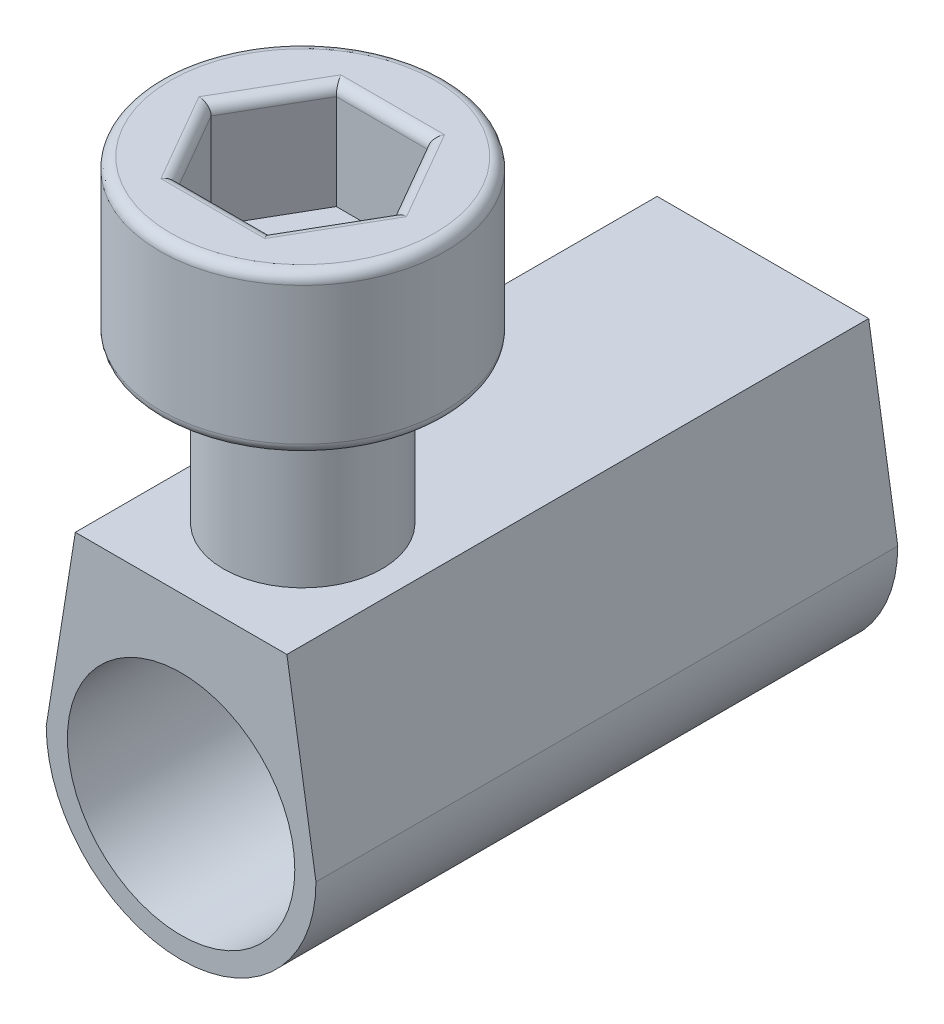
SolidWorks part; units mm, degrees
ref_plane "Спереди" through (0, 0, 0) normal (0, 0, 1) x (1, 0, 0)
ref_plane "Сверху" through (0, 0, 0) normal (0, 1, 0) x (1, 0, 0)
ref_plane "Справа" through (0, 0, 0) normal (1, 0, 0) x (0, 0, -1)
sketch "Эскиз1" plane through (0, 0, 0) normal (0, 0, 1) x (1, 0, 0)
  line L0 (-2, 6) -> (2, 6)
  line L1 (2, 6) -> (2.55, 2.55)
  line L3 (-2.55, 2.55) -> (-2, 6)
  circle A0 centre (0, 2.55) radius 2.15
  circle A1 centre (0, 2.55) radius 2.55 construction
  arc A2 (2.55, 2.55) -> (-2.55, 2.55) centre (0, 2.55) cw
  point P3 (0, 6)
  point P5 (0, 0)
  dimension "D2" = 2.55
  dimension "D3" = 4.3
  dimension "D1" = 6
  dimension "D4" = 4
extrude "Бобышка-Вытянуть1" add sketch "Эскиз1" against normal blind 11
sketch "Эскиз2" plane through (0, 6, 0) normal (0, 1, 0) x (1, 0, 0)
  line L0 (2, 0) -> (-2, 0) construction
  circle A0 centre (0, 2.3) radius 1.5
  dimension "D1" = 2.3
  dimension "D2" = 3
extrude "Вырез-Вытянуть1" cut sketch "Эскиз2" against normal up to next
sketch "Эскиз3" plane through (0, 6, 0) normal (0, 1, 0) x (1, 0, 0)
  circle A0 centre (0, 2.3) radius 1.5
extrude "Бобышка-Вытянуть2" add sketch "Эскиз3" along normal blind 3 and the other way blind 2 separate body
sketch "Эскиз4" plane through (0, 9, 0) normal (0, 1, 0) x (1, 0, 0)
  circle A0 centre (0, 2.3) radius 2.7
extrude "Бобышка-Вытянуть3" add sketch "Эскиз4" along normal blind 3
sketch "Эскиз5" plane through (0, 12, 0) normal (0, 1, 0) x (1, 0, 0)
  line L1 (1.7321, 2.3) -> (0.866, 3.8)
  line L2 (0.866, 3.8) -> (-0.866, 3.8)
  line L3 (-0.866, 3.8) -> (-1.7321, 2.3)
  line L4 (-1.7321, 2.3) -> (-0.866, 0.8)
  line L5 (-0.866, 0.8) -> (0.866, 0.8)
  line L6 (0.866, 0.8) -> (1.7321, 2.3)
  circle A0 centre (0, 2.3) radius 1.5 construction
extrude "Вырез-Вытянуть2" cut sketch "Эскиз5" against normal blind 2
fillet "Скругление1" radius 0.2 9 edges at (0, 9, 0.4) (0, 9, -0.8) (0, 12, 0.4) (1.299, 12, -3.05) (0, 12, -3.8) (-1.299, 12, -3.05) (-1.299, 12, -1.55) (0, 12, -0.8) (1.299, 12, -1.55)
